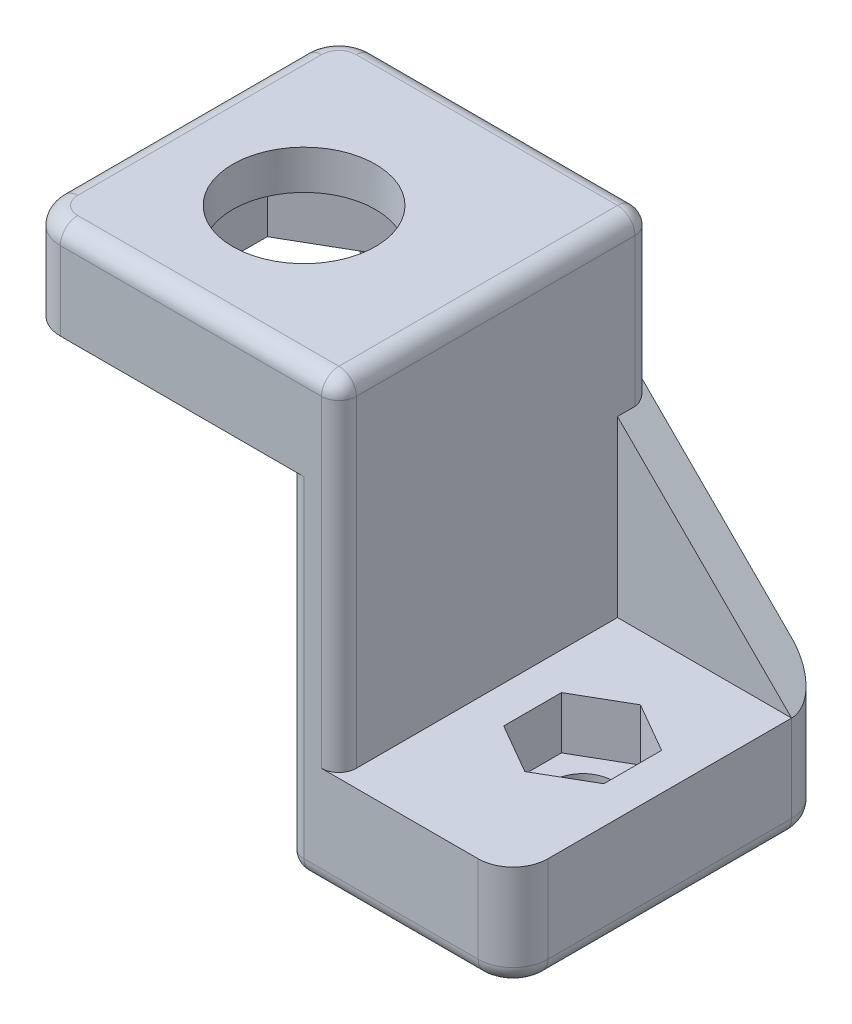
SolidWorks part; units mm, degrees
ref_plane "Front Plane" through (0, 0, 0) normal (0, 0, 1) x (1, 0, 0)
ref_plane "Top Plane" through (0, 0, 0) normal (0, 1, 0) x (1, 0, 0)
ref_plane "Right Plane" through (0, 0, 0) normal (1, 0, 0) x (0, 0, -1)
sketch "Sketch1" plane through (0, 0, 0) normal (0, 0, 1) x (1, 0, 0)
  line L0 (0, 0) -> (0, 40)
  line L1 (0, 40) -> (-30, 40)
  line L2 (-30, 40) -> (-30, 51)
  line L3 (-30, 51) -> (6, 51)
  line L4 (6, 51) -> (6, 12)
  line L5 (6, 12) -> (26, 12)
  line L6 (26, 12) -> (26, 0)
  line L7 (26, 0) -> (0, 0)
  dimension "D1" = 11
  dimension "D2" = 36
  dimension "D3" = 20
  dimension "D4" = 12
  dimension "D5" = 6
  dimension "D6" = 40
extrude "Boss-Extrude1" add sketch "Sketch1" along normal blind 36
sketch "Sketch3" plane through (0, 12, 0) normal (0, 1, 0) x (1, 0, 0)
  line L0 (16, -18) -> (26, -18) construction
  line L1 (26, -36) -> (26, 0) construction
  line L2 (16, -18) -> (6, -18) construction
  line L3 (6, -36) -> (6, 0) construction
  line L4 (16, -18) -> (16, 0) construction
  line L5 (26, 0) -> (6, 0) construction
  line L6 (16, -18) -> (16, -36) construction
  line L7 (26, -36) -> (6, -36) construction
  circle A0 centre (16, -18) radius 3.5
  dimension "D1" = 7
extrude "Cut-Extrude1" cut sketch "Sketch3" against normal blind 32
sketch "Sketch2" plane through (0, 51, 0) normal (0, 1, 0) x (1, 0, 0)
  line L0 (-30, -36) -> (-30, 0) construction
  line L3 (6, -36) -> (-30, -36) construction
  circle A0 centre (-14, -20) radius 8.2
  dimension "D1" = 16.4
  dimension "D2" = 16
  dimension "D3" = 16
extrude "Cut-Extrude2" cut sketch "Sketch2" against normal blind 32
sketch "Sketch4" plane through (0, 12, 0) normal (0, 1, 0) x (1, 0, 0)
  line L0 (26, -36) -> (26, 0) construction
  line L1 (16, -24.6395) -> (21.75, -21.3198)
  line L2 (21.75, -21.3198) -> (21.75, -14.6802)
  line L3 (21.75, -14.6802) -> (16, -11.3605)
  line L4 (16, -11.3605) -> (10.25, -14.6802)
  line L5 (10.25, -14.6802) -> (10.25, -21.3198)
  line L6 (10.25, -21.3198) -> (16, -24.6395)
  circle A0 centre (16, -18) radius 5.75 construction
  dimension "D1" = 11.5
extrude "Cut-Extrude3" cut sketch "Sketch4" against normal blind 6
sketch "Sketch5" plane through (0, 0, 0) normal (0, 0, -1) x (-1, 0, 0)
  line L0 (-26, 12) -> (-6, 32)
  line L1 (-6, 32) -> (-6, 12)
  line L2 (-6, 12) -> (-26, 12)
  line L3 (0, 10) -> (0, 40)
  line L4 (0, 40) -> (30, 40)
  line L5 (30, 40) -> (0, 10)
  line L6 (-6, 12) -> (-6, 51) construction
  line L7 (0, 40) -> (0, 0) construction
  dimension "D1" = 30
  dimension "D2" = 20
extrude "Boss-Extrude3" add sketch "Sketch5" against normal blind 4
sketch "Sketch6" plane through (0, 40, 0) normal (0, -1, 0) x (1, 0, 0)
  line L1 (-14, 8.453) -> (-4, 14.2265)
  line L2 (-4, 14.2265) -> (-4, 25.7735)
  line L3 (-4, 25.7735) -> (-14, 31.547)
  line L4 (-14, 31.547) -> (-24, 25.7735)
  line L5 (-24, 25.7735) -> (-24, 14.2265)
  line L6 (-24, 14.2265) -> (-14, 8.453)
  circle A0 centre (-14, 20) radius 10 construction
  circle A1 centre (-14, 20) radius 8.2 construction
  dimension "D1" = 20
extrude "Cut-Extrude4" cut sketch "Sketch6" against normal blind 6.5
fillet "Fillet1" radius 4 4 edges at (26, 6, 36) (26, 6, 0) (-30, 45.5, 36) (-30, 45.5, 0)
fillet "Fillet4" radius 2 15 edges at (11, 0, 36) (24.8284, 0, 34.8284) (11, 0, 0) (24.8284, 0, 1.1716) (-10, 51, 0) (-28.8284, 51, 1.1716) (-30, 51, 18) (-28.8284, 51, 34.8284) (6, 41.5, 0) (0, 20, 36) (26, 0, 18) (0, 0, 18) (-10, 51, 36) (6, 31.5, 36) (6, 51, 18)
